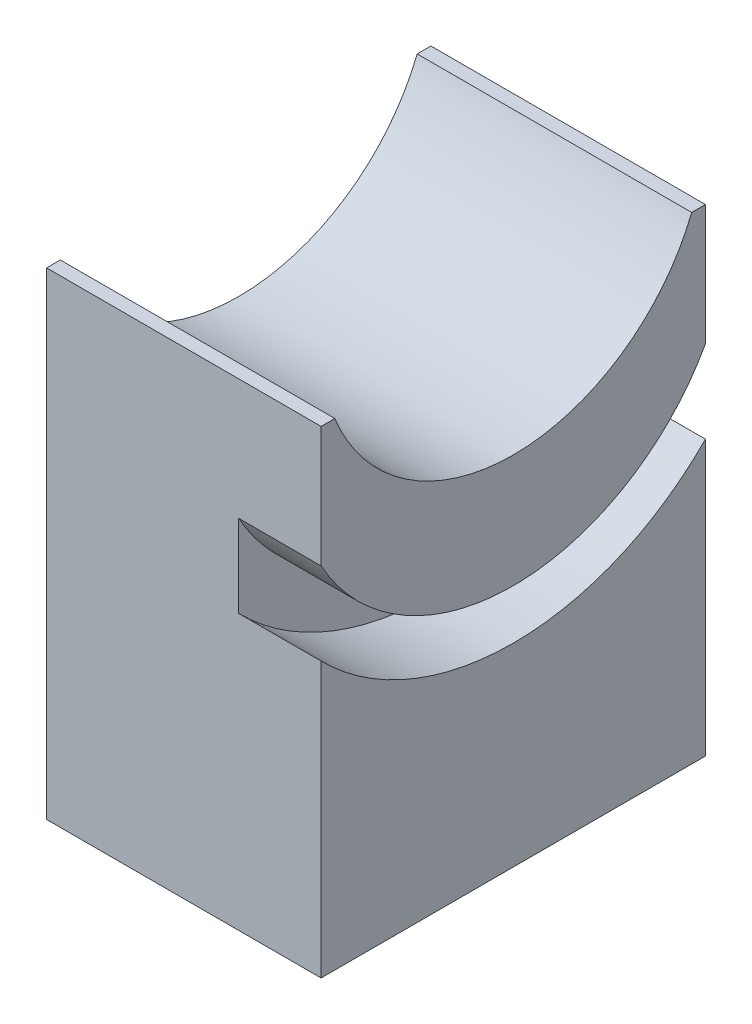
SolidWorks part; units mm, degrees
ref_plane "Front Plane" through (0, 0, 0) normal (0, 0, 1) x (1, 0, 0)
ref_plane "Top Plane" through (0, 0, 0) normal (0, 1, 0) x (1, 0, 0)
ref_plane "Right Plane" through (0, 0, 0) normal (1, 0, 0) x (0, 0, -1)
sketch "Sketch1" plane through (0, 0, 0) normal (1, 0, 0) x (0, 0, -1)
  line L0 (0, 0) -> (-28, 0)
  line L3 (-27, 34.8038) -> (-28, 34.8038)
  line L4 (-28, 34.8038) -> (-28, 0)
  line L5 (-1, 34.8038) -> (0, 34.8038)
  line L6 (0, 34.8038) -> (0, 0)
  arc A1 (-1, 34.8038) -> (-27, 34.8038) centre (-14, 40) cw
  point P6 (-2, 34.8038)
  point P9 (-30, 0)
  point P10 (-22.1914, 29.537)
  point P11 (-15.8523, 28.9608)
  point P12 (-16.5109, 29.0431)
  point P13 (-15, 28.3845)
  point P14 (-30, 34.2296)
  point P15 (-28, 0)
  point P16 (-28, 34.8038)
  dimension "D1" = 14
  dimension "D2" = 1
  dimension "D3" = 28
  dimension "D4" = 40
extrude "Boss-Extrude2" add sketch "Sketch1" against normal blind 20
sketch "Sketch3" plane through (0, 0, 0) normal (1, 0, 0) x (0, 0, -1)
  line L0 (-28, 34.8038) -> (-28, 0) construction
  line L1 (0, 0) -> (0, 34.8038) construction
  line L3 (-28, 20) -> (-28, 26)
  line L5 (0, 26) -> (0, 20)
  arc A0 (-28, 26) -> (0, 26) centre (-14, 33.746) ccw
  arc A1 (-28, 20) -> (0, 20) centre (-14, 33.746) ccw
  dimension "D2" = 16
  dimension "D3" = 20
  dimension "D1" = 6
  dimension "D4" = 6
extrude "Cut-Extrude1" cut sketch "Sketch3" against normal blind 6
